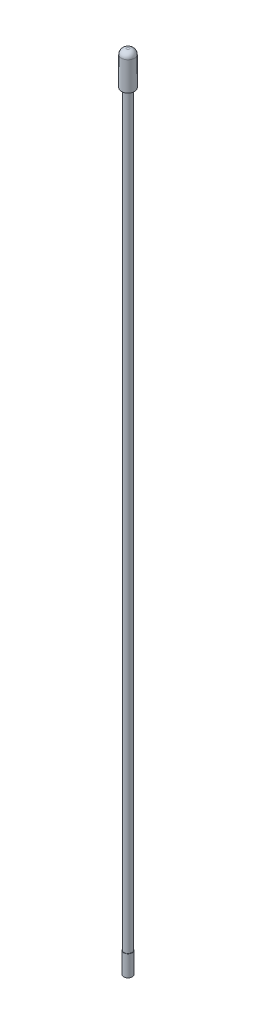
SolidWorks part; units mm, degrees
ref_plane "Front Plane" through (0, 0, 0) normal (0, 0, 1) x (1, 0, 0)
ref_plane "Top Plane" through (0, 0, 0) normal (0, 1, 0) x (1, 0, 0)
ref_plane "Right Plane" through (0, 0, 0) normal (1, 0, 0) x (0, 0, -1)
sketch "Sketch2" plane through (0, 0, 0) normal (0, 1, 0) x (1, 0, 0)
  circle A0 centre (0, 0) radius 1.625
  dimension "D1" = 3.25
extrude "Boss-Extrude2" add sketch "Sketch2" along normal blind 8 contours A0
sketch "Sketch4" plane through (0, 8, 0) normal (0, 1, 0) x (1, 0, 0)
  circle A0 centre (0, 0) radius 1.5
  dimension "D1" = 3
extrude "Boss-Extrude3" add sketch "Sketch4" along normal blind 285 contours A0
sketch "Sketch5" plane through (0, 293, 0) normal (0, 1, 0) x (1, 0, 0)
  circle A0 centre (0, 0) radius 2.5
  dimension "D1" = 5
extrude "Boss-Extrude4" add sketch "Sketch5" along normal blind 13
fillet "Fillet1" radius 2 1 edges at (0, 306, 2.5)
